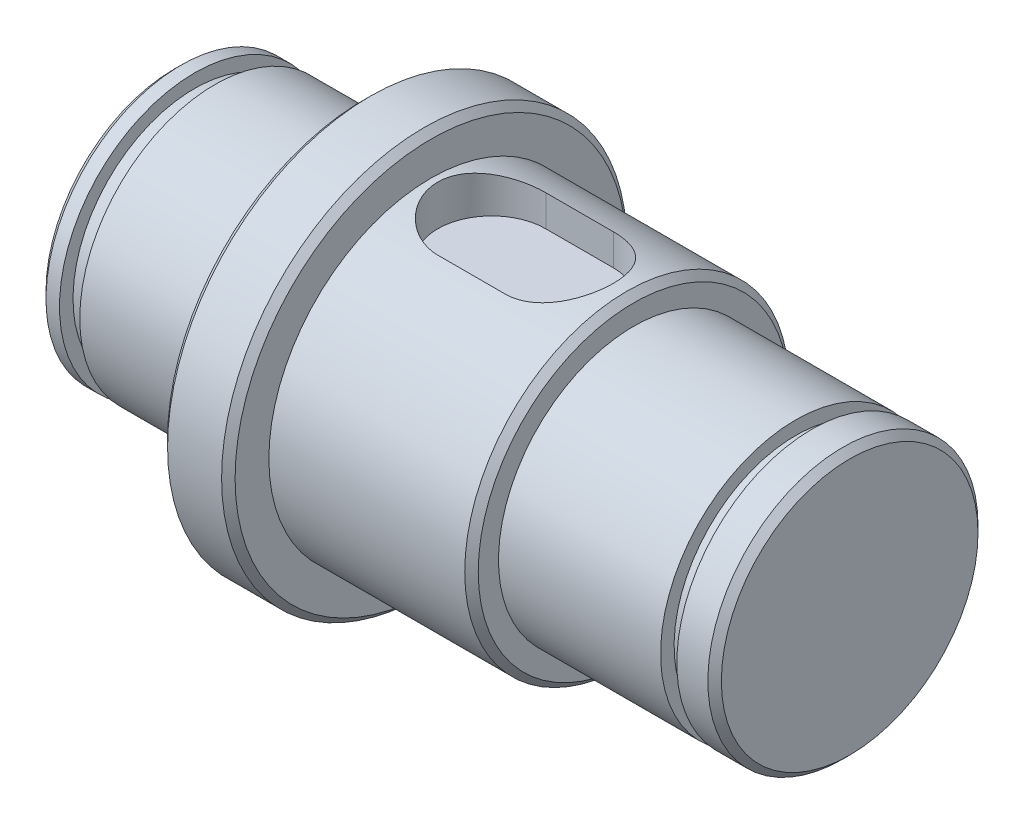
SolidWorks part; units mm, degrees
ref_plane "Piano frontale" through (0, 0, 0) normal (0, 0, 1) x (1, 0, 0)
ref_plane "Piano superiore" through (0, 0, 0) normal (0, 1, 0) x (1, 0, 0)
ref_plane "Piano destro" through (0, 0, 0) normal (1, 0, 0) x (0, 0, -1)
sketch "Schizzo1" plane through (0, 0, 0) normal (1, 0, 0) x (0, 0, -1)
  circle A0 centre (0, 0) radius 10
  dimension "D1" = 20
extrude "Estrusione-Estrusione1" add sketch "Schizzo1" along normal mid plane 50
sketch "Schizzo2" plane through (25, 0, 0) normal (1, 0, 0) x (0, 0, -1)
  circle A0 centre (0, 0) radius 10 construction
  circle A1 centre (0, 0) radius 10
  circle A2 centre (0, 0) radius 12
  dimension "D1" = 24
extrude "Estrusione-Estrusione2" add sketch "Schizzo2" against normal blind 15 from offset 16 offset against normal yes
sketch "Schizzo3" plane through (-25, 0, 0) normal (-1, 0, 0) x (0, 0, 1)
  circle A0 centre (0, 0) radius 15
  circle A1 centre (0, 0) radius 10
  circle A2 centre (0, 0) radius 10
  dimension "D2" = 30
  dimension "D1" = 0
extrude "Estrusione-Estrusione3" add sketch "Schizzo3" against normal up to surface (5 mm away) from offset 14 up to face at (-6, 0, -10) offset against normal yes
sketch "Schizzo5" plane through (0, 0, 0) normal (0, 1, 0) x (1, 0, 0)
  line L0 (-1.5, 0) -> (3.5, 0) construction
  line L3 (-1.5, 4) -> (3.5, 4)
  line L4 (-1.5, -4) -> (3.5, -4)
  line L5 (-6, -12) -> (-6, 12) construction
  line L6 (-6, -15) -> (-6, 15) construction
  arc A2 (-1.5, 4) -> (-1.5, -4) centre (-1.5, 0) ccw
  arc A3 (3.5, -4) -> (3.5, 4) centre (3.5, 0) ccw
  circle A5 centre (-1.5, 0) radius 4 construction
  point P2 (1, 0)
  dimension "D3" = 8
  dimension "D1" = 4.5
  dimension "D2" = 9.5
extrude "Taglio-Estrusione1" cut sketch "Schizzo5" along normal up to next from offset 9
chamfer "Smusso1" distance 0.5 angle 45 5 edges at (-25, 0, -10) (-11, 0, 15) (-6, 0, -15) (9, 0, -12) (25, 0, -10)
sketch "Schizzo6" plane through (0, 0, 0) normal (0, 0, 1) x (1, 0, 0)
  line L0 (-25, 0) -> (25, 0) construction
  line L1 (-25, 9.5) -> (-25, -9.5) construction
  point P0 (-25, 0)
  point P4 (0, 0)
sketch "Schizzo7" plane through (0, 0, 0) normal (0, 0, 1) x (1, 0, 0)
  line L0 (24.5, 10) -> (9, 10) construction
  line L1 (22.2, 10) -> (21, 10)
  line L2 (22.2, 10) -> (22.2, 9)
  line L3 (22.2, 9) -> (21, 9)
  line L4 (21, 10) -> (21, 9)
  line L5 (-11, 10) -> (-24.5, 10) construction
  line L6 (-23.5, 10) -> (-22, 10)
  line L7 (-23.5, 10) -> (-23.5, 9)
  line L8 (-23.5, 9) -> (-22, 9)
  line L9 (-22, 10) -> (-22, 9)
  line L10 (-24.5, 10) -> (-24.5, -10) construction
  line L11 (24.5, -10) -> (24.5, 10) construction
  line L12 (-25, 0) -> (25, 0) construction
  dimension "D1" = 1
  dimension "D2" = 2.3
  dimension "D3" = 1.5
  dimension "D4" = 1.2
  dimension "D5" = 9
revolve "Taglia-Rivoluzione1" cut sketch "Schizzo7" angle 360 about L0
